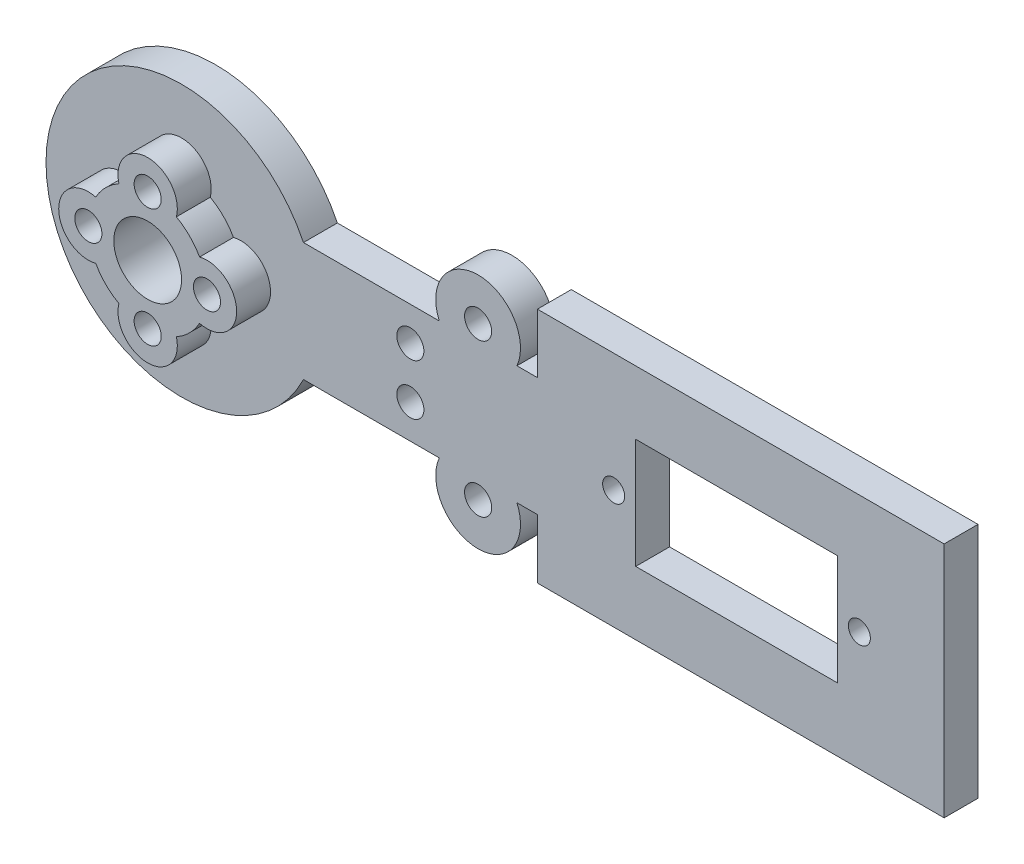
SolidWorks part; units mm, degrees
ref_plane "Front Plane" through (0, 0, 0) normal (0, 0, 1) x (1, 0, 0)
ref_plane "Top Plane" through (0, 0, 0) normal (0, 1, 0) x (1, 0, 0)
ref_plane "Right Plane" through (0, 0, 0) normal (1, 0, 0) x (0, 0, -1)
sketch "Main_web_profile" plane through (0, 0, 0) normal (0, 0, 1) x (1, 0, 0)
  line L1 (0, -7) -> (60, -7)
  line L2 (0, -7) -> (0, 7)
  line L3 (0, 7) -> (60, 7)
  line L4 (60, -7) -> (60, 7)
  dimension "D1" = 60
  dimension "D2" = 14
extrude "Main_web" add sketch "Main_web_profile" along normal blind 4
sketch "Shoulder_horn_flange_profile" plane through (0, 0, 0) normal (0, 0, 1) x (1, 0, 0)
  circle A0 centre (0, 0) radius 16
  dimension "D1" = 32
extrude "Shoulder_horn_flange" add sketch "Shoulder_horn_flange_profile" along normal blind 4
sketch "Elbow_servo_mount_profile" plane through (0, 0, 0) normal (0, 0, 1) x (1, 0, 0)
  line L1 (42, -14) -> (90, -14)
  line L2 (42, -14) -> (42, 14)
  line L3 (42, 14) -> (90, 14)
  line L4 (90, -14) -> (90, 14)
  dimension "D1" = 48
  dimension "D2" = 28
extrude "Elbow_servo_mount" add sketch "Elbow_servo_mount_profile" along normal blind 4
sketch "SG90_body_clearance_profile" plane through (0, 0, 0) normal (0, 0, 1) x (1, 0, 0)
  line L1 (53.6, -6.5) -> (77.4, -6.5)
  line L2 (53.6, -6.5) -> (53.6, 6.5)
  line L3 (53.6, 6.5) -> (77.4, 6.5)
  line L4 (77.4, -6.5) -> (77.4, 6.5)
  dimension "D1" = 23.8
  dimension "D2" = 13
extrude "SG90_body_clearance" cut sketch "SG90_body_clearance_profile" along normal through all from offset 5
sketch "Elbow_tab_fasteners_profile" plane through (0, 0, 0) normal (0, 0, 1) x (1, 0, 0)
  circle A0 centre (51, 0) radius 1.3
  circle A1 centre (80, 0) radius 1.3
  dimension "D1" = 2.6
  dimension "D2" = 2.6
extrude "Elbow_tab_fasteners" cut sketch "Elbow_tab_fasteners_profile" along normal through all from offset 50
sketch "Shoulder_center_screw_access_profile" plane through (0, 0, 0) normal (0, 0, 1) x (1, 0, 0)
  circle A0 centre (0, 0) radius 4
  dimension "D1" = 8
extrude "Shoulder_center_screw_access" cut sketch "Shoulder_center_screw_access_profile" along normal through all from offset 50
sketch "Cable_tie_holes_profile" plane through (0, 0, 0) normal (0, 0, 1) x (1, 0, 0)
  circle A0 centre (27, -3) radius 1.6
  circle A1 centre (27, 3) radius 1.6
  dimension "D1" = 3.2
  dimension "D2" = 3.2
extrude "Cable_tie_holes" cut sketch "Cable_tie_holes_profile" along normal through all from offset 50
sketch "Passive_lower_mount_boss_profile" plane through (0, 0, 0) normal (0, 0, 1) x (1, 0, 0)
  circle A0 centre (35, -9) radius 5
  dimension "D1" = 10
extrude "Passive_lower_mount_boss" add sketch "Passive_lower_mount_boss_profile" along normal blind 4
sketch "Passive_upper_mount_boss_profile" plane through (0, 0, 0) normal (0, 0, 1) x (1, 0, 0)
  circle A0 centre (35, 9) radius 5
  dimension "D1" = 10
extrude "Passive_upper_mount_boss" add sketch "Passive_upper_mount_boss_profile" along normal blind 4
sketch "Passive_cheek_standoffs_profile" plane through (0, 0, 0) normal (0, 0, 1) x (1, 0, 0)
  circle A0 centre (35, -9) radius 1.6
  circle A1 centre (35, 9) radius 1.6
  dimension "D1" = 3.2
  dimension "D2" = 3.2
extrude "Passive_cheek_standoffs" cut sketch "Passive_cheek_standoffs_profile" along normal through all from offset 50
sketch "Shoulder_dowel_support_hub_profile" plane through (0, 0, 0) normal (0, 0, 1) x (1, 0, 0)
  circle A0 centre (0, 0) radius 7
  circle A1 centre (0, 0) radius 4
  dimension "D1" = 14
  dimension "D2" = 8
extrude "Shoulder_dowel_support_hub" add sketch "Shoulder_dowel_support_hub_profile" along normal blind 4 from offset 4
sketch "Raised_M3_washer_seats_PCD14_profile" plane through (0, 0, 0) normal (0, 0, 1) x (1, 0, 0)
  circle A0 centre (7, 0) radius 3.5
  circle A1 centre (-7, 0) radius 3.5
  circle A2 centre (0, 7) radius 3.5
  circle A3 centre (0, -7) radius 3.5
  dimension "D1" = 7
  dimension "D2" = 7
  dimension "D3" = 7
  dimension "D4" = 7
extrude "Raised_M3_washer_seats_height8" add sketch "Raised_M3_washer_seats_PCD14_profile" along normal blind 4 from offset 4
sketch "Metal_horn_M3_clearance_PCD14_profile" plane through (0, 0, 0) normal (0, 0, 1) x (1, 0, 0)
  circle A0 centre (7, 0) radius 1.6
  circle A1 centre (-7, 0) radius 1.6
  circle A2 centre (0, 7) radius 1.6
  circle A3 centre (0, -7) radius 1.6
  dimension "D1" = 3.2
  dimension "D2" = 3.2
  dimension "D3" = 3.2
  dimension "D4" = 3.2
extrude "Metal_horn_M3_clearance_PCD14" cut sketch "Metal_horn_M3_clearance_PCD14_profile" along normal through all from offset 50
sketch "Restore_shoulder_sleeve_bore_profile" plane through (0, 0, 0) normal (0, 0, 1) x (1, 0, 0)
  circle A0 centre (0, 0) radius 4
  dimension "D1" = 8
extrude "Restore_shoulder_sleeve_bore" cut sketch "Restore_shoulder_sleeve_bore_profile" along normal through all from offset 50
